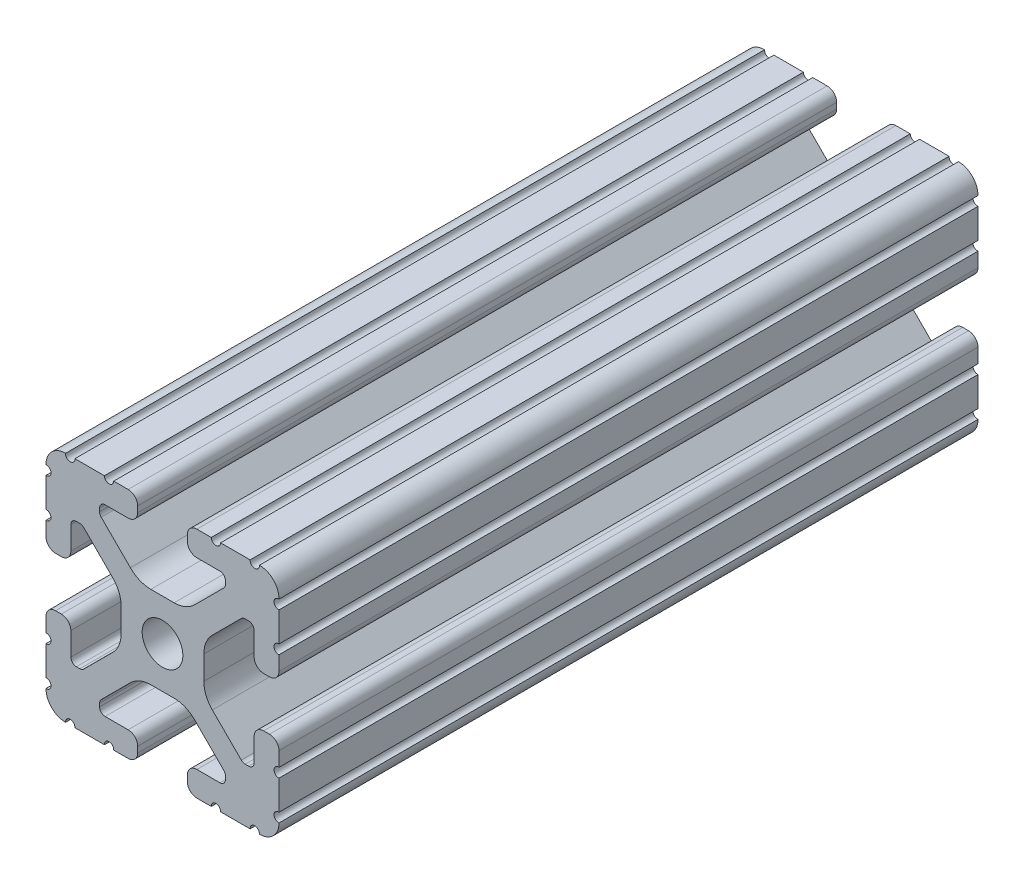
SolidWorks part; units mm, degrees
material "6061 Alloy"
ref_plane "Front Plane" through (0, 0, 0) normal (0, 0, 1) x (1, 0, 0)
ref_plane "Top Plane" through (0, 0, 0) normal (0, 1, 0) x (1, 0, 0)
ref_plane "Right Plane" through (0, 0, 0) normal (1, 0, 0) x (0, 0, -1)
sketch "Sketch1" plane through (0, 0, 0) normal (0, 0, 1) x (1, 0, 0)
  line L0 (0, 25.6181) -> (0, -24.623) construction
  line L1 (-20.8943, 0) -> (20.4607, 0) construction
  line L2 (-10.0229, 12.9148) -> (-5.2522, 8.144)
  line L3 (-10.287, 14.0843) -> (-10.287, 13.5524)
  line L4 (-5.6176, 14.986) -> (-9.3853, 14.986)
  line L5 (-4.064, 17.4964) -> (-4.064, 16.5396)
  line L6 (-7.9742, 19.05) -> (-5.6176, 19.05)
  line L7 (-14.3277, 19.05) -> (-9.4982, 19.05)
  line L8 (-19.05, 9.4961) -> (-19.05, 14.3277)
  line L9 (-19.05, 5.6176) -> (-19.05, 7.9763)
  line L10 (-16.5396, 4.064) -> (-17.4964, 4.064)
  line L11 (-14.986, 9.3853) -> (-14.986, 5.6176)
  line L12 (-13.516, 10.287) -> (-14.0843, 10.287)
  line L13 (-8.1476, 5.2921) -> (-12.8784, 10.0229)
  line L14 (-6.7564, -1.9335) -> (-6.7564, 1.9335)
  line L15 (-12.8784, -10.0229) -> (-8.1476, -5.2921)
  line L16 (-14.0843, -10.287) -> (-13.516, -10.287)
  line L17 (-14.986, -5.6176) -> (-14.986, -9.3853)
  line L18 (-17.4964, -4.064) -> (-16.5396, -4.064)
  line L19 (-19.05, -7.9763) -> (-19.05, -5.6176)
  line L20 (-19.05, -14.3277) -> (-19.05, -9.4961)
  line L21 (-9.4961, -19.05) -> (-14.3277, -19.05)
  line L22 (-5.6176, -19.05) -> (-7.9763, -19.05)
  line L23 (-4.064, -17.4964) -> (-4.064, -16.5396)
  line L24 (10.0229, -12.9148) -> (5.2522, -8.144)
  line L25 (10.287, -14.0843) -> (10.287, -13.5524)
  line L26 (5.6176, -14.986) -> (9.3853, -14.986)
  line L28 (-1.9022, 6.7564) -> (1.9022, 6.7564)
  line L29 (-1.9022, -6.7564) -> (1.9022, -6.7564)
  line L31 (-5.6176, -14.986) -> (-9.3853, -14.986)
  line L32 (-10.287, -14.0843) -> (-10.287, -13.5524)
  line L33 (-10.0229, -12.9148) -> (-5.2522, -8.144)
  line L66 (4.064, -16.5396) -> (4.064, -17.4964)
  line L67 (5.6176, -19.05) -> (7.9763, -19.05)
  line L68 (9.4961, -19.05) -> (14.3277, -19.05)
  line L69 (19.05, -14.3277) -> (19.05, -9.4961)
  line L70 (19.05, -7.9763) -> (19.05, -5.6176)
  line L71 (17.4964, -4.064) -> (16.5396, -4.064)
  line L72 (14.986, -5.6176) -> (14.986, -9.3853)
  line L73 (14.0843, -10.287) -> (13.516, -10.287)
  line L74 (12.8784, -10.0229) -> (8.1476, -5.2921)
  line L75 (6.7564, -1.9335) -> (6.7564, 1.9335)
  line L76 (8.1476, 5.2921) -> (12.8784, 10.0229)
  line L77 (13.516, 10.287) -> (14.0843, 10.287)
  line L78 (14.986, 9.3853) -> (14.986, 5.6176)
  line L79 (16.5396, 4.064) -> (17.4964, 4.064)
  line L80 (19.05, 5.6176) -> (19.05, 7.9763)
  line L81 (19.05, 9.4961) -> (19.05, 14.3277)
  line L82 (14.3277, 19.05) -> (9.4982, 19.05)
  line L83 (7.9742, 19.05) -> (5.6176, 19.05)
  line L84 (4.064, 17.4964) -> (4.064, 16.5396)
  line L85 (5.6176, 14.986) -> (9.3853, 14.986)
  line L86 (10.287, 14.0843) -> (10.287, 13.5524)
  line L87 (10.0229, 12.9148) -> (5.2522, 8.144)
  arc A0 (-10.0229, 12.9148) -> (-10.287, 13.5524) centre (-9.3853, 13.5524) cw
  circle A1 centre (0, 0) radius 3.3274
  arc A2 (-10.287, 14.0843) -> (-9.3853, 14.986) centre (-9.3853, 14.0843) cw
  arc A3 (-4.064, 16.5396) -> (-5.6176, 14.986) centre (-5.6176, 16.5396) cw
  arc A4 (-5.6176, 19.05) -> (-4.064, 17.4964) centre (-5.6176, 17.4964) cw
  arc A5 (-7.9742, 19.05) -> (-9.4982, 19.05) centre (-8.7362, 19.05) cw
  arc A6 (-14.3277, 19.05) -> (-15.8475, 19.05) centre (-15.0876, 18.9933) cw
  arc A7 (-19.05, 15.8475) -> (-15.8475, 19.05) centre (-15.8751, 15.8751) cw
  arc A8 (-19.05, 15.8475) -> (-19.05, 14.3277) centre (-18.9933, 15.0876) cw
  arc A9 (-19.05, 9.4961) -> (-19.05, 7.9763) centre (-18.9933, 8.7362) cw
  arc A10 (-17.4964, 4.064) -> (-19.05, 5.6176) centre (-17.4964, 5.6176) cw
  arc A11 (-14.986, 5.6176) -> (-16.5396, 4.064) centre (-16.5396, 5.6176) cw
  arc A12 (-14.986, 9.3853) -> (-14.0843, 10.287) centre (-14.0843, 9.3853) cw
  arc A13 (-13.516, 10.287) -> (-12.8784, 10.0229) centre (-13.516, 9.3853) cw
  arc A14 (-8.1476, 5.2921) -> (-6.7564, 1.9335) centre (-11.5062, 1.9335) cw
  arc A15 (-6.7564, -1.9335) -> (-8.1476, -5.2921) centre (-11.5062, -1.9335) cw
  arc A16 (-12.8784, -10.0229) -> (-13.516, -10.287) centre (-13.516, -9.3853) cw
  arc A17 (-14.0843, -10.287) -> (-14.986, -9.3853) centre (-14.0843, -9.3853) cw
  arc A18 (-16.5396, -4.064) -> (-14.986, -5.6176) centre (-16.5396, -5.6176) cw
  arc A19 (-19.05, -5.6176) -> (-17.4964, -4.064) centre (-17.4964, -5.6176) cw
  arc A20 (-19.05, -7.9763) -> (-19.05, -9.4961) centre (-18.9933, -8.7362) cw
  arc A21 (-19.05, -14.3277) -> (-19.05, -15.8475) centre (-18.9933, -15.0876) cw
  arc A22 (-15.8475, -19.05) -> (-19.05, -15.8475) centre (-15.8751, -15.8751) cw
  arc A23 (-15.8475, -19.05) -> (-14.3277, -19.05) centre (-15.0876, -18.9933) cw
  arc A24 (-9.4961, -19.05) -> (-7.9763, -19.05) centre (-8.7362, -18.9933) cw
  arc A25 (-4.064, -17.4964) -> (-5.6176, -19.05) centre (-5.6176, -17.4964) cw
  arc A26 (-5.2522, -8.144) -> (-1.9022, -6.7564) centre (-1.9022, -11.494) cw
  arc A27 (1.9022, -6.7564) -> (5.2522, -8.144) centre (1.9022, -11.494) cw
  arc A28 (10.0229, -12.9148) -> (10.287, -13.5524) centre (9.3853, -13.5524) cw
  arc A29 (10.287, -14.0843) -> (9.3853, -14.986) centre (9.3853, -14.0843) cw
  arc A30 (4.064, -16.5396) -> (5.6176, -14.986) centre (5.6176, -16.5396) cw
  arc A31 (-4.064, -16.5396) -> (-5.6176, -14.986) centre (-5.6176, -16.5396) ccw
  arc A32 (-10.287, -14.0843) -> (-9.3853, -14.986) centre (-9.3853, -14.0843) ccw
  arc A33 (-10.0229, -12.9148) -> (-10.287, -13.5524) centre (-9.3853, -13.5524) ccw
  arc A79 (4.064, -17.4964) -> (5.6176, -19.05) centre (5.6176, -17.4964) ccw
  arc A80 (9.4961, -19.05) -> (7.9763, -19.05) centre (8.7362, -18.9933) ccw
  arc A81 (15.8475, -19.05) -> (14.3277, -19.05) centre (15.0876, -18.9933) ccw
  arc A82 (15.8475, -19.05) -> (19.05, -15.8475) centre (15.8751, -15.8751) ccw
  arc A83 (19.05, -14.3277) -> (19.05, -15.8475) centre (18.9933, -15.0876) ccw
  arc A84 (19.05, -7.9763) -> (19.05, -9.4961) centre (18.9933, -8.7362) ccw
  arc A85 (19.05, -5.6176) -> (17.4964, -4.064) centre (17.4964, -5.6176) ccw
  arc A86 (16.5396, -4.064) -> (14.986, -5.6176) centre (16.5396, -5.6176) ccw
  arc A87 (14.0843, -10.287) -> (14.986, -9.3853) centre (14.0843, -9.3853) ccw
  arc A88 (12.8784, -10.0229) -> (13.516, -10.287) centre (13.516, -9.3853) ccw
  arc A89 (6.7564, -1.9335) -> (8.1476, -5.2921) centre (11.5062, -1.9335) ccw
  arc A90 (8.1476, 5.2921) -> (6.7564, 1.9335) centre (11.5062, 1.9335) ccw
  arc A91 (13.516, 10.287) -> (12.8784, 10.0229) centre (13.516, 9.3853) ccw
  arc A92 (14.986, 9.3853) -> (14.0843, 10.287) centre (14.0843, 9.3853) ccw
  arc A93 (14.986, 5.6176) -> (16.5396, 4.064) centre (16.5396, 5.6176) ccw
  arc A94 (17.4964, 4.064) -> (19.05, 5.6176) centre (17.4964, 5.6176) ccw
  arc A95 (19.05, 9.4961) -> (19.05, 7.9763) centre (18.9933, 8.7362) ccw
  arc A96 (19.05, 15.8475) -> (19.05, 14.3277) centre (18.9933, 15.0876) ccw
  arc A97 (19.05, 15.8475) -> (15.8475, 19.05) centre (15.8751, 15.8751) ccw
  arc A98 (14.3277, 19.05) -> (15.8475, 19.05) centre (15.0876, 18.9933) ccw
  arc A99 (7.9742, 19.05) -> (9.4982, 19.05) centre (8.7362, 19.05) ccw
  arc A100 (5.6176, 19.05) -> (4.064, 17.4964) centre (5.6176, 17.4964) ccw
  arc A101 (4.064, 16.5396) -> (5.6176, 14.986) centre (5.6176, 16.5396) ccw
  arc A102 (10.287, 14.0843) -> (9.3853, 14.986) centre (9.3853, 14.0843) ccw
  arc A103 (10.0229, 12.9148) -> (10.287, 13.5524) centre (9.3853, 13.5524) ccw
  arc A104 (1.9022, 6.7564) -> (5.2522, 8.144) centre (1.9022, 11.494) ccw
  arc A105 (-5.2522, 8.144) -> (-1.9022, 6.7564) centre (-1.9022, 11.494) ccw
  dimension "D1" = 6.6548
  dimension "D2" = 19.05
  dimension "D3" = 38.1
  dimension "D4" = 20.574
  dimension "D5" = 13.5128
  dimension "D6" = 4.064
  dimension "D7" = 8.128
  dimension "D8" = 4.064
  dimension "D9" = 12.2936
extrude "Extrude1" add sketch "Sketch1" against normal blind 114.3
